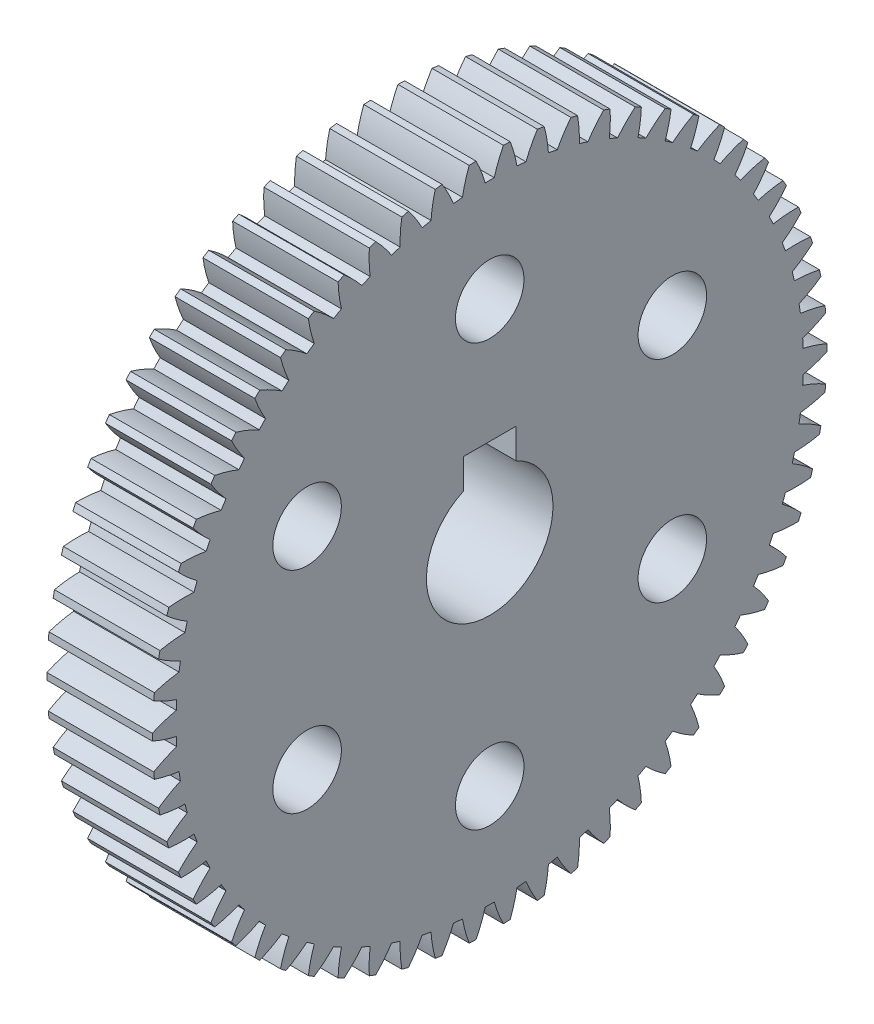
SolidWorks part; units mm, degrees
ref_plane "Plane1" through (0, 0, 0) normal (0, 0, 1) x (1, 0, 0)
ref_plane "Plane2" through (0, 0, 0) normal (0, 1, 0) x (1, 0, 0)
ref_plane "Plane3" through (0, 0, 0) normal (1, 0, 0) x (0, 0, -1)
other "Configuration Table"
sketch "HoldingSke" plane through (0, 0, 0) normal (0, 1, 0) x (1, 0, 0)
  line L0 (0, 0) -> (0.4695, -0.8829)
  line L1 (-15, 0) -> (100, 0) construction
  line L2 (0, 0) -> (-2.1039, 2.3779)
  line L3 (0, 0) -> (-11.863, 4.5341)
  line L4 (0, 0) -> (4.0544, 7.6251)
  line L5 (0, 0) -> (-46.8476, -17.4728)
  line L6 (0, 0) -> (-8.2896, -5.593)
  line L7 (-2.1039, 2.3779) -> (8.6586, 51.2059)
  line L8 (-76.2, 54.61) -> (-73.9, 54.61)
  line L9 (-71.009, 38.7566) -> (-53.1078, 45.2721)
  line L10 (-76.2, 71.12) -> (104.1128, 71.12)
  line L11 (0, 0) -> (-10, 0)
  line L12 (-76.2, 101.6) -> (-76.162, 101.6)
  line L13 (24.9733, 27.94) -> (52.9518, 28.4284)
  line L14 (24.9733, 27.94) -> (24.9743, 27.94)
  line L15 (24.9733, 27.94) -> (100.4006, 29.5858)
  line L16 (-63.627, -1) -> (-12.827, -1)
  circle A0 centre (0, 0) radius 6
  circle A1 centre (0, 0) radius 29.749
  circle A2 centre (0, 0) radius 37.5
  circle A3 centre (0, 0) radius 6
  dimension "MHD" = 59.498
  dimension "Hub_dia" = 75
  dimension "Bore" = 12
  dimension "MBD" = 12
  dimension "Num_teeth" = 62
  dimension "Pitch" = 1
  dimension "Overall_len" = 50
  dimension "Show_teeth" = 62
  dimension "Thickness" = 10
  dimension "OAL" = 50.0001
  dimension "T_dim" = 2.3
  dimension "Ap" = 20
  dimension "H" = 19.05
  dimension "Pitch_radius" = 180.3128
  dimension "Width" = 10
  dimension "Backlash" = 0.038
  dimension "Addendum_fac" = 1
  dimension "Dedendum_fac" = 1.25
  dimension "Clearance_fac" = 0.25
  dimension "Dedendum_add" = 0.001
  dimension "Module" = 1
sketch "BasProSke" plane through (0, 0, 0) normal (0, 1, 0) x (1, 0, 0)
  line L0 (-10, 0) -> (60, 0) construction
  line L1 (0, 0) -> (0, 32)
  line L2 (0, 0) -> (10, 0)
  line L3 (10, 0) -> (10, 32)
  line L4 (10, 32) -> (0, 32)
  dimension "Thickness" = 10
  dimension "Diameter" = 64
revolve "Base-Revolve" add sketch "BasProSke" angle 360 about L0
sketch "TooCutSke" plane through (0, 0, 0) normal (1, 0, 0) x (0, 0, -1)
  line L1 (0, 0) -> (0, 107) construction
  line L2 (0, 0) -> (-0.8518, 30.9883) construction
  line L3 (0, 0) -> (-3.1394, 61.9038) construction
  line L4 (-0.8518, 30.9883) -> (-1.5697, 30.9519) construction
  arc A0 (0.4289, 29.7459) -> (-0.4289, 29.7459) centre (0, 0) ccw
  arc A1 (1.31, 31.9986) -> (-1.31, 31.9986) centre (0, 0) ccw
  circle A2 centre (0, 0) radius 31 construction
  circle A3 centre (0, 0) radius 29.1305 construction
  arc A4 (-0.4289, 29.7459) -> (-1.31, 31.9986) centre (-12.3625, 26.3771) ccw
  arc A5 (1.31, 31.9986) -> (0.4289, 29.7459) centre (12.3625, 26.3771) ccw
  dimension "Root_dia" = 59.498
  dimension "Overcut_dia" = 64.0508
  dimension "Pitch_dia" = 62
  dimension "Base_dia" = 58.2609
  dimension "Flank_rad" = 12.4
  dimension "Half_ang" = 2.903
  dimension "Half_CT" = 0.7188
extrude "ToothCut" cut sketch "TooCutSke" along normal through all
fillet "Breaks" [suppressed] radius 0.02
fillet "RootFillets" [suppressed] radius 0.251
pattern_circular "TeethCuts" count 62 every 5.806 about axis through (-10, 0, 0) along (1, 0, 0) of "ToothCut", "RootFillets", "Breaks"
sketch "HubNeaOneSke" plane through (0, 0, 0) normal (-1, 0, 0) x (0, 0, 1)
  circle A0 centre (0, 0) radius 29.749
  dimension "Diameter" = 59.498
extrude "HubNearOne" [suppressed] add sketch "HubNeaOneSke" along normal blind 40.0001
sketch "HubNeaBotSke" plane through (0, 0, 0) normal (-1, 0, 0) x (0, 0, 1)
  circle A0 centre (0, 0) radius 29.749
  dimension "Diameter" = 59.498
extrude "HubNearBoth" [suppressed] add sketch "HubNeaBotSke" along normal blind 20
ref_plane "FarPln" through (10, 0, 0) normal (1, 0, 0) x (0, 0, -1)
sketch "HubFarSke" plane through (10, 0, 0) normal (1, 0, 0) x (0, 0, -1)
  circle A0 centre (0, 0) radius 29.749
  dimension "Diameter" = 59.498
extrude "HubFar" [suppressed] add sketch "HubFarSke" along normal blind 20
sketch "BorSke" plane through (0, 0, 0) normal (1, 0, 0) x (0, 0, -1)
  circle A0 centre (0, 0) radius 6
  dimension "Diameter" = 12
extrude "Bore" cut sketch "BorSke" along normal mid plane 100.0001
sketch "KeySke" plane through (0, 0, 0) normal (1, 0, 0) x (0, 0, -1)
  line L0 (-2.5, 0) -> (-2.5, 8.3)
  line L1 (-2.5, 8.3) -> (2.5, 8.3)
  line L2 (2.5, 8.3) -> (2.5, 0)
  line L3 (0, 0) -> (0, 34) construction
  line L4 (-2.5, 0) -> (2.5, 0)
  dimension "Offset" = 8.3
  dimension "Width" = 5
extrude "Keyway" cut sketch "KeySke" along normal mid plane 100.0001
pattern_circular "Keyway2" [suppressed] count 2 every 90 about axis through (-10, 0, 0) along (1, 0, 0)
sketch "Sketch1" plane through (0, 0, 0) normal (-1, 0, 0) x (0, 0, 1)
  circle A0 centre (0, 0) radius 20 construction
  circle A1 centre (0, 20) radius 3.25
  dimension "D1" = 40
  dimension "D2" = 6.5
extrude "Cut-Extrude1" cut sketch "Sketch1" against normal through all
pattern_circular "CirPattern1" count 6 over 360 about axis through (0, 0, 0) along (1, 0, 0) of "Cut-Extrude1"
equation "' \"Module@HoldingSke\" = 6.35"
equation "' \"Num_teeth@HoldingSke\" = 12"
equation "' \"Ap@HoldingSke\" =  20"
equation "' \"Ap@HoldingSke\" = 20"
equation "' \"Width@HoldingSke\" = 0.5 * 25.4"
equation "' \"Hub_dia@HoldingSke\"= 1 * 25.4"
equation "' \"Hub_dia@HoldingSke\" = 1 * 25.4"
equation "' \"Overall_len@HoldingSke\" = 1.0 * 25.4"
equation "' \"Bore@HoldingSke\" = 0.75 * 25.4"
equation "' \"T_dim@HoldingSke\" = 0.1 * 25.4"
equation "' \"Width@KeySke\" = 0.25 * 25.4"
equation "' \"Show_teeth@HoldingSke\" = 13"
equation "' \"Backlash@HoldingSke\" = 0.009 * 25.4"
equation "' \"Addendum_fac@HoldingSke\" = 1.0"
equation "' \"Dedendum_fac@HoldingSke\" = 1.25"
equation "' \"Dedendum_add@HoldingSke\" = 0.00005 * 25.4"
equation "' \"Clearance_fac@HoldingSke\" = 0.25"
equation "\"Pitch@HoldingSke\" = 1 / \"Module@HoldingSke\""
equation "\"Overcut_dia@TooCutSke\" = (\"Num_teeth@HoldingSke\" + 2 * \"Addendum_fac@HoldingSke\") / \"Pitch@HoldingSke\" + 0.002 * 25.4"
equation "\"Pitch_dia@TooCutSke\" = \"Num_teeth@HoldingSke\" / \"Pitch@HoldingSke\""
equation "\"Base_dia@TooCutSke\" = \"Num_teeth@HoldingSke\" / \"Pitch@HoldingSke\" * cos((\"Ap@HoldingSke\"  * 3.14159265 / 180))"
equation "\"Root_dia@TooCutSke\" = (\"Num_teeth@HoldingSke\" + 2) / \"Pitch@HoldingSke\" - 2 * (\"Addendum_fac@HoldingSke\" + \"Dedendum_fac@HoldingSke\") / \"Pitch@HoldingSke\" - \"Dedendum_add@HoldingSke\" * 2"
equation "\"Half_ang@TooCutSke\" = 180 / \"Num_teeth@HoldingSke\""
equation "\"Half_CT@TooCutSke\" = \"Num_teeth@HoldingSke\" / \"Pitch@HoldingSke\" * sin((3.14159265 / 2 / \"Num_teeth@HoldingSke\")) / 2 - 7 * \"Backlash@HoldingSke\" / 4"
equation "\"Flank_rad@TooCutSke\" = \"Num_teeth@HoldingSke\" / \"Pitch@HoldingSke\" / 5"
equation "\"Radius@RootFillets\" = \"Clearance_fac@HoldingSke\" / \"Pitch@HoldingSke\" + \"Dedendum_add@HoldingSke\""
equation "\"Break_rad@Breaks\" = 0.02 / \"Pitch@HoldingSke\""
equation "\"Thickness@HoldingSke\" = \"Width@HoldingSke\""
equation "\"OAL@HoldingSke\" = \"Thickness@HoldingSke\""
equation "\"MHD@HoldingSke\" = (\"Num_teeth@HoldingSke\" + 2) / \"Pitch@HoldingSke\" - 2 * (\"Addendum_fac@HoldingSke\" + \"Dedendum_fac@HoldingSke\")  / \"Pitch@HoldingSke\" - \"Dedendum_add@HoldingSke\" * 2"
equation "\"MBD@HoldingSke\" = (\"Num_teeth@HoldingSke\" + 2) / \"Pitch@HoldingSke\" - 2 * (\"Addendum_fac@HoldingSke\" + \"Dedendum_fac@HoldingSke\")  / \"Pitch@HoldingSke\" - \"Dedendum_add@HoldingSke\" * 2 - 0.002 * 25.4"
equation "\"MHD@HoldingSke\" = ((sgn( \"MHD@HoldingSke\" - \"Hub_dia@HoldingSke\" )-1)*( \"MHD@HoldingSke\" - \"Hub_dia@HoldingSke\" ))/-2+ \"Hub_dia@HoldingSke\""
equation "\"MBD@HoldingSke\" = ((sgn( \"MBD@HoldingSke\" - \"Bore@HoldingSke\" )-1)*( \"MBD@HoldingSke\" - \"Bore@HoldingSke\" ))/-2+ \"Bore@HoldingSke\""
equation "\"OAL@HoldingSke\" = ((sgn( \"OAL@HoldingSke\" - \"Overall_len@HoldingSke\" )+1)*( \"OAL@HoldingSke\" - \"Overall_len@HoldingSke\" ))/2 + \"Overall_len@HoldingSke\" + 0.000002 * 25.4"
equation "\"Num_teeth@TeethCuts\" = int( \"Show_teeth@HoldingSke\" ) + 1"
equation "\"Num_teeth@TeethCuts\" = ((sgn( \"Num_teeth@TeethCuts\" - \"Num_teeth@HoldingSke\" )-1)*( \"Num_teeth@TeethCuts\" - \"Num_teeth@HoldingSke\" ))/-2+ \"Num_teeth@HoldingSke\""
equation "\"Num_teeth@TeethCuts\" = ((sgn( \"Num_teeth@TeethCuts\" - 2.0)+1)*( \"Num_teeth@TeethCuts\" - 2.0))/2 +2.0"
equation "\"Angle@TeethCuts\" = 360.0 / \"Num_teeth@HoldingSke\""
equation "\"Diameter@BasProSke\" = (\"Num_teeth@HoldingSke\" + 2 * \"Addendum_fac@HoldingSke\") / \"Pitch@HoldingSke\""
equation "\"Thickness@BasProSke\"  = \"Thickness@HoldingSke\""
equation "' \"Fillet_rad@BasProSke\" =  \"Thickness@HoldingSke\" * 0.05"
equation "' \"Fillet_rad@BasProSke\" = \"Thickness@HoldingSke\" * 0.05"
equation "\"MHD@HoldingSke\" = ((sgn( \"MHD@HoldingSke\" - \"Root_dia@TooCutSke\" )-1)*( \"MHD@HoldingSke\" - \"Root_dia@TooCutSke\" ))/-2+ \"Root_dia@TooCutSke\""
equation "\"Diameter@HubNeaOneSke\" = \"MHD@HoldingSke\""
equation "\"Length@HubNearOne\" = \"OAL@HoldingSke\" - \"Thickness@BasProSke\""
equation "\"Diameter@HubNeaBotSke\" = \"MHD@HoldingSke\""
equation "\"Length@HubNearBoth\" = ( \"OAL@HoldingSke\" - \"Thickness@BasProSke\" ) / 2.0"
equation "\"Thickness@FarPln\" = \"Thickness@BasProSke\""
equation "\"Diameter@HubFarSke\" = \"MHD@HoldingSke\""
equation "\"Length@HubFar\" = ( \"OAL@HoldingSke\" - \"Thickness@BasProSke\" ) / 2.0"
equation "\"Diameter@BorSke\" = \"MBD@HoldingSke\""
equation "\"D1@Bore\" = \"OAL@HoldingSke\" * 2.0"
equation "\"D1@Keyway\" = \"OAL@HoldingSke\" * 2.0"
equation "\"Offset@KeySke\" = \"T_dim@HoldingSke\" + \"MBD@HoldingSke\" / 2.0"
